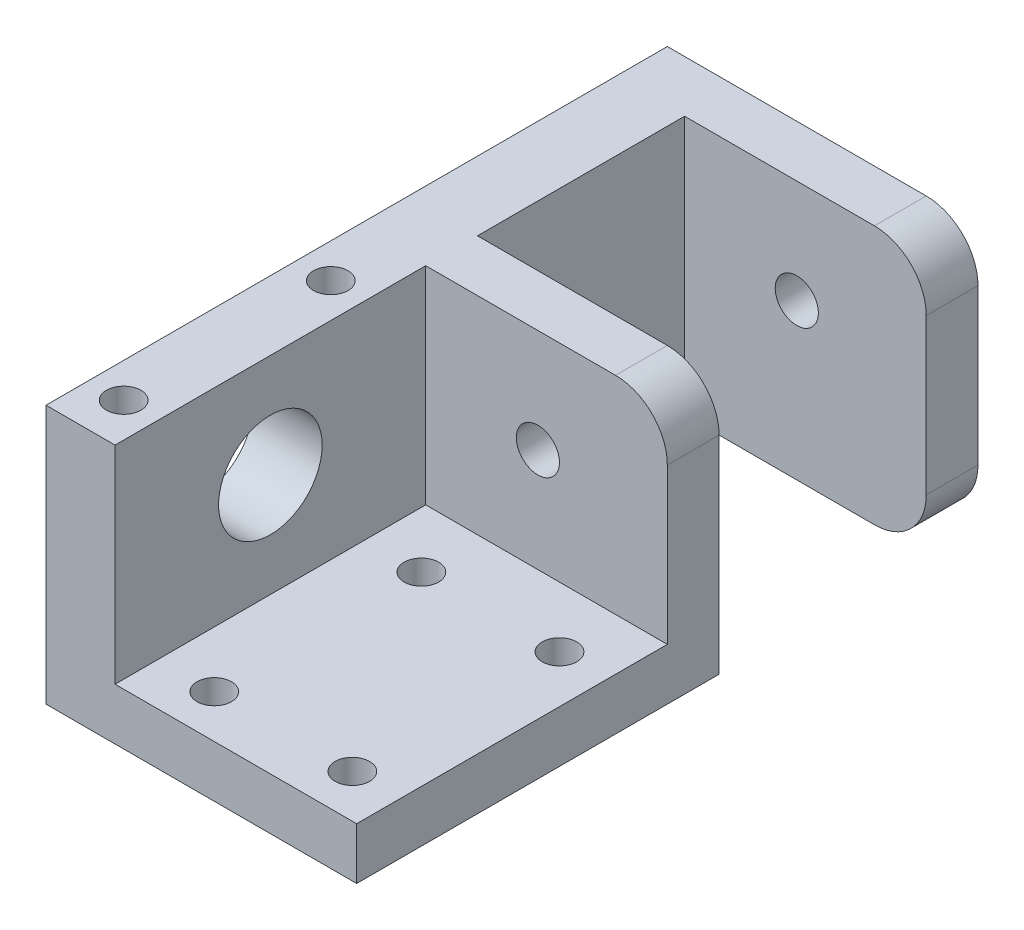
SolidWorks part; units mm, degrees
ref_plane "前视基准面" through (0, 0, 0) normal (0, 0, 1) x (1, 0, 0)
ref_plane "上视基准面" through (0, 0, 0) normal (0, 1, 0) x (1, 0, 0)
ref_plane "右视基准面" through (0, 0, 0) normal (1, 0, 0) x (0, 0, -1)
other "Configuration Table"
sketch "草图2" plane through (0, 0, 0) normal (0, 1, 0) x (1, 0, 0)
  line L12 (18, 0) -> (0, 0)
  line L13 (0, 0) -> (0, 18)
  line L14 (0, 18) -> (18, 18)
  line L15 (18, 18) -> (18, 15)
  line L16 (18, 15) -> (4, 15)
  line L17 (4, 15) -> (4, 3)
  line L18 (4, 3) -> (18, 3)
  line L19 (18, 3) -> (18, 0)
  dimension "D1" = 18
  dimension "D2" = 18
  dimension "D3" = 18
  dimension "D5" = 4
  dimension "D6" = 3
  dimension "D7" = 3
extrude "凸台-拉伸2" add sketch "草图2" along normal blind 15 contours L14 L15 L16 L17 L18 L19 L12 L13
fillet "圆角1" radius 3 3 edges at (18, 0, -16.5) (18, 15, -16.5) (18, 15, -1.5)
sketch "草图4" plane through (0, 0, -18) normal (0, 0, -1) x (-1, 0, 0)
  line L0 (0, 15) -> (-15, 15) construction
  line L2 (-18, 12) -> (-18, 3) construction
  circle A0 centre (-10.5, 9) radius 1.25
  dimension "D1" = 2.5
  dimension "D2" = 6
  dimension "D3" = 7.5
extrude "切除-拉伸1" cut sketch "草图4" against normal up to surface (18 mm away) up to face at (10.3243, 8.5243, 0)
sketch "草图5" plane through (0, 15, 0) normal (0, 1, 0) x (1, 0, 0)
  line L0 (0, 0) -> (0, -18)
  line L1 (0, -18) -> (18, -18)
  line L2 (18, -18) -> (18, 0)
  line L3 (0, 0) -> (18, 0)
  line L4 (15, 0) -> (18, 0) construction
  dimension "D1" = 18
  dimension "D2" = 18
extrude "凸台-拉伸3" add sketch "草图5" against normal blind 3 from offset 12 contours L2 L3 L0 L1 offset against normal yes
sketch "草图6" plane through (0, 3, 0) normal (0, 1, 0) x (1, 0, 0)
  line L0 (0, -18) -> (18, -18) construction
  line L1 (0, 0) -> (4, 0)
  line L2 (0, 0) -> (0, -18)
  line L3 (0, -18) -> (4, -18)
  line L4 (4, 0) -> (4, -18)
  dimension "D1" = 4
extrude "凸台-拉伸5" add sketch "草图6" along normal blind 12 contours L4 L3 L2 L1
sketch "草图8" plane through (4, 0, 0) normal (1, 0, 0) x (0, 0, -1)
  line L0 (0, 15) -> (-18, 15) construction
  line L2 (-18, 15) -> (-18, 3) construction
  circle A0 centre (-9, 9) radius 3
  dimension "D1" = 6
  dimension "D2" = 6
  dimension "D3" = 9
extrude "切除-拉伸2" cut sketch "草图8" against normal through all
sketch "草图9" plane through (0, 3, 0) normal (0, 1, 0) x (1, 0, 0)
  circle A0 centre (7.25, -15.5) radius 1
  circle A1 centre (15.25, -15.5) radius 1
  circle A2 centre (7.25, -3.5) radius 1
  circle A3 centre (15.25, -3.5) radius 1
  dimension "D1" = 2
  dimension "D2" = 2
  dimension "D3" = 2
  dimension "D4" = 2
extrude "切除-拉伸3" cut sketch "草图9" against normal through all
sketch "草图10" plane through (0, 15, 0) normal (0, 1, 0) x (1, 0, 0)
  line L0 (4, 0) -> (4, -18) construction
  line L1 (0, -18) -> (4, -18) construction
  circle A0 centre (2, -15.5) radius 1
  circle A1 centre (2, -3.5) radius 1
  dimension "D1" = 2
  dimension "D2" = 2
  dimension "D6" = 12
  dimension "D3" = 2
  dimension "D4" = 2
  dimension "D5" = 2.5
extrude "切除-拉伸4" cut sketch "草图10" against normal blind 5
